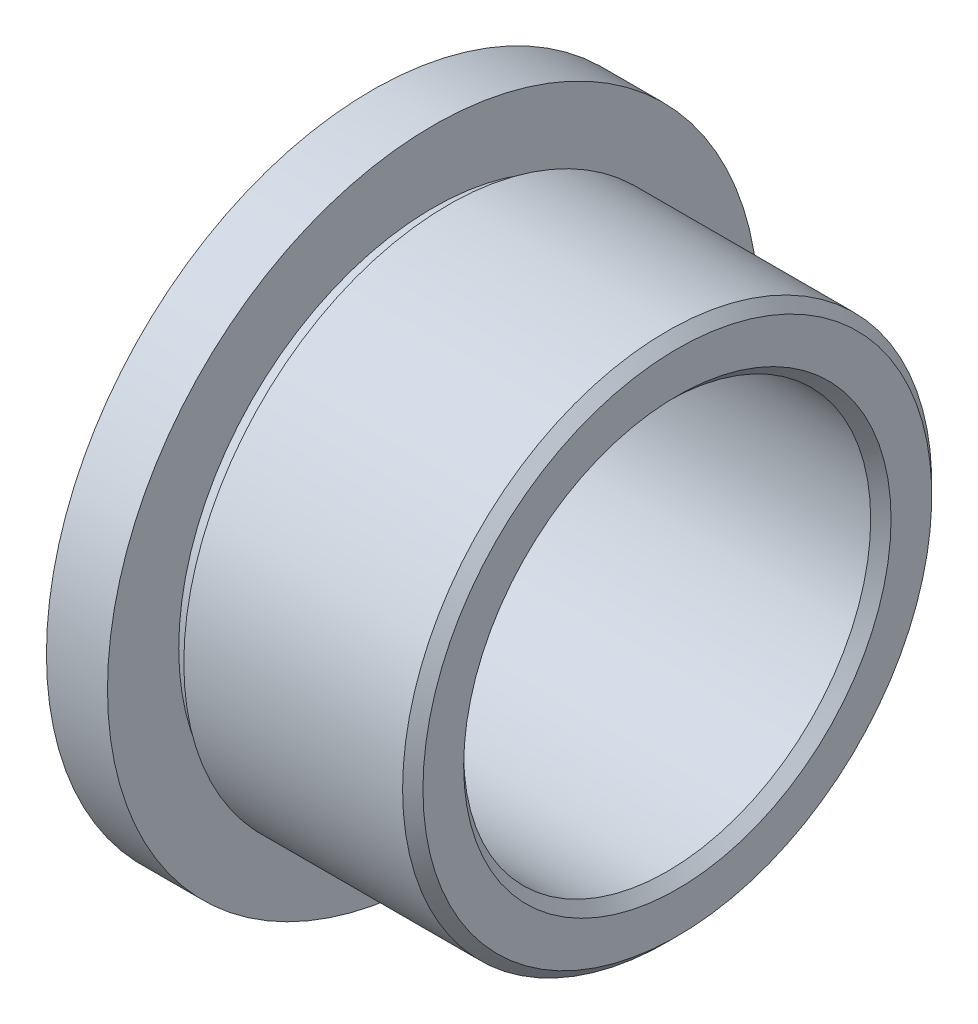
SolidWorks part; units mm, degrees
ref_plane "Přední rovina" through (0, 0, 0) normal (0, 0, 1) x (1, 0, 0)
ref_plane "Vrchní rovina" through (0, 0, 0) normal (0, 1, 0) x (1, 0, 0)
ref_plane "Pravá rovina" through (0, 0, 0) normal (1, 0, 0) x (0, 0, -1)
sketch "Skica1" plane through (0, 0, 0) normal (0, 0, 1) x (1, 0, 0)
  line L0 (0, 16) -> (0, 10)
  line L1 (0, 10) -> (15, 10)
  line L2 (15, 10) -> (15, 13)
  line L3 (15, 13) -> (3.75, 13)
  line L4 (3.75, 13) -> (3.75, 12.5)
  line L5 (3.75, 12.5) -> (3, 12.5)
  line L6 (3, 12.5) -> (3, 16)
  line L7 (3, 16) -> (0, 16)
  line L8 (0, 0) -> (15, 0) construction
  dimension "D1" = 32
  dimension "d_" = 20
  dimension "L" = 15
  dimension "b" = 3
  dimension "D" = 26
  dimension "D2" = 0.5
  dimension "D3" = 0.75
revolve "Otočit kolem osy1" add sketch "Skica1" angle 360 about L8
chamfer "Zkosit1" distance 0.5 angle 45 3 edges at (0, 0, 10) (15, 0, 10) (15, 0, 13)
equation "\"D2@Skica1\" = \"D1@Zkosit1\" "
equation "\"D3@Skica1\" = \"D1@Zkosit1\"*1.5"
